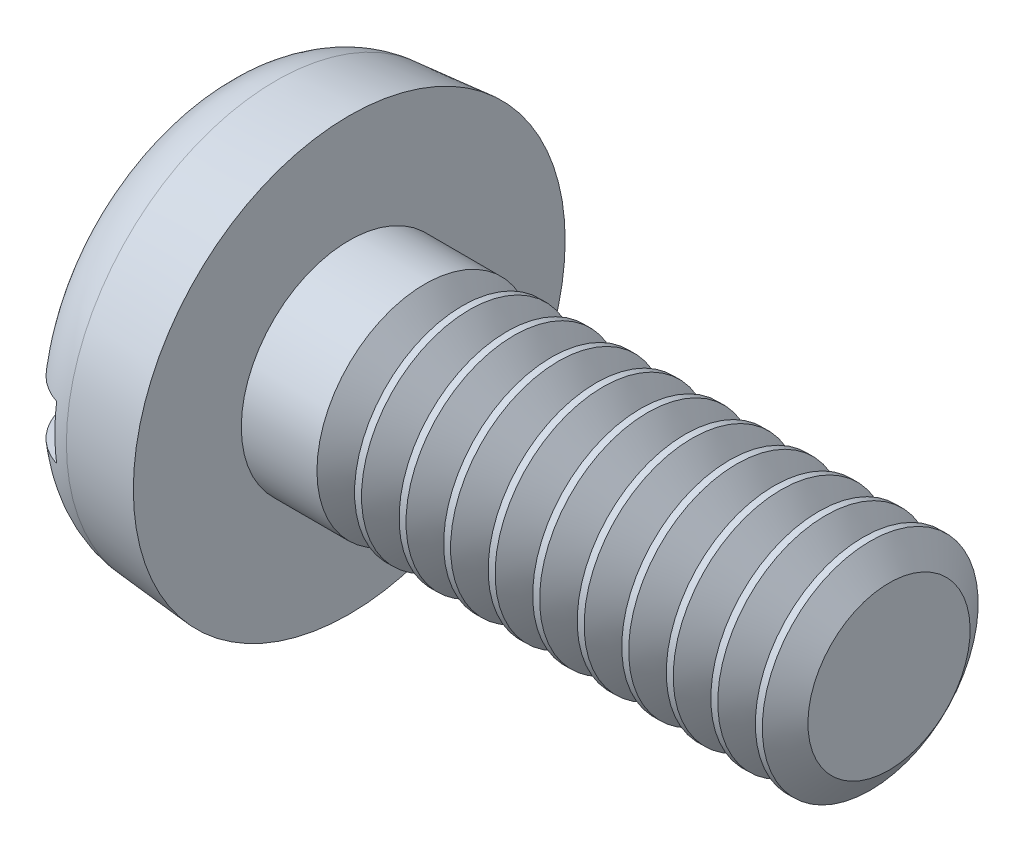
SolidWorks part; units mm, degrees
ref_plane "Plane1" through (0, 0, 0) normal (0, 0, 1) x (1, 0, 0)
ref_plane "Plane2" through (0, 0, 0) normal (0, 1, 0) x (1, 0, 0)
ref_plane "Plane3" through (0, 0, 0) normal (1, 0, 0) x (0, 0, -1)
sketch "BodySke" plane through (0, 0, 0) normal (0, 0, 1) x (1, 0, 0)
  line L0 (1, 0.8) -> (1, 1.6)
  line L1 (0, 0) -> (0, 1.5125)
  line L2 (-25.4, 0) -> (127, 0) construction
  line L3 (5, 0) -> (0, 0)
  line L4 (1, 0.8) -> (5, 0.8)
  line L5 (5, 0.8) -> (5, 0)
  line L6 (0, 1.5125) -> (1, 1.6)
  line L9 (1.35, 2.3875) -> (1.35, -7.1375) construction
  line L10 (0, 6.35) -> (0, -3.175) construction
  dimension "Head_ht" = 1
  dimension "Diameter" = 1.6
  dimension "Length" = 4
  dimension "Head_dia" = 3.2
  dimension "Advance" = 0.35
  dimension "Thread_nom" = 5
  dimension "Head_side_angle" = 5
revolve "Base-Revolve" add sketch "BodySke"
cosmetic thread "ThreadCosmetic" [suppressed]
fillet "Fillet1" [suppressed] radius 0.1
fillet "Fillet2" radius 0.5 1 edges at (0, 0, 1.5125)
sketch "Sketch2" plane through (0, 0, 0) normal (1, 0, 0) x (0, 0, -1)
  line L0 (1.6, -0.2) -> (-1.6, -0.2)
  line L1 (1.6, -0.2) -> (1.6, 0.2)
  line L2 (-1.6, 0.2) -> (1.6, 0.2)
  line L3 (-1.6, 0.2) -> (-1.6, -0.2)
  dimension "D1" = 3.2
  dimension "D2" = 1.6
  dimension "Slot_width" = 0.4
  dimension "D3" = 0.2
extrude "Slot" cut sketch "Sketch2" along normal blind 0.35
sketch "ThdSchSke" plane through (0, 0, 0) normal (0, 0, 1) x (1, 0, 0)
  line L0 (1.7, -0.601) -> (1.5607, -0.8)
  line L1 (1.7, -0.601) -> (1.8393, -0.8)
  line L2 (1.8393, -0.8) -> (1.8393, -1)
  line L3 (-3.175, 0) -> (5.1513, 0) construction
  line L5 (1.8393, -1) -> (1.5607, -1)
  line L6 (1.5607, -1) -> (1.5607, -0.8)
  dimension "Thread_minor" = 1.202
  dimension "Diameter" = 1.6
  dimension "Start" = 1.7
  dimension "SideAngle" = 55
  dimension "VeeAngle" = 70
  dimension "Overcut" = 2
revolve "ThreadSchematic" cut sketch "ThdSchSke" angle 360 about L3
pattern_linear "ThdSchPat" count 11 spacing 0.33 along (1, 0, 0) of "ThreadSchematic"
equation "\"D1@Sketch2\" = \"Head_dia@BodySke\""
equation "\"D2@Sketch2\" = \"D1@Sketch2\" / 2"
equation "\"D3@Sketch2\" = \"Slot_width@Sketch2\" / 2"
equation "\"Thread_length@ThreadCosmetic\" = ((sgn( (\"Length@BodySke\" - \"Advance@BodySke\" * 2.0 ) - \"Thread_nom@BodySke\" )-1)*( (\"Length@BodySke\" - \"Advance@BodySke\"  * 2.0) - \"Thread_nom@BodySke\" ))/-2+ \"Thread_nom@BodySke\""
equation "\"Thread_minor@ThdSchSke\" = \"Thread_minor@ThreadCosmetic\""
equation "\"Diameter@ThdSchSke\" = \"Diameter@BodySke\""
equation "\"Overcut@ThdSchSke\" = \"Diameter@BodySke\" * 1.25"
equation "\"Start@ThdSchSke\" = \"Head_ht@BodySke\" + \"Length@BodySke\" - \"Thread_length@ThreadCosmetic\"  '---Non-countersunk---"
equation "\"Num_threads@ThdSchPat\" = int( \"Thread_length@ThreadCosmetic\" / \"Advance@BodySke\" + 0.999 )  + 1"
equation "\"Advance@ThdSchPat\" = \"Thread_length@ThreadCosmetic\" /  (\"Num_threads@ThdSchPat\" - 1) 'relax it"
